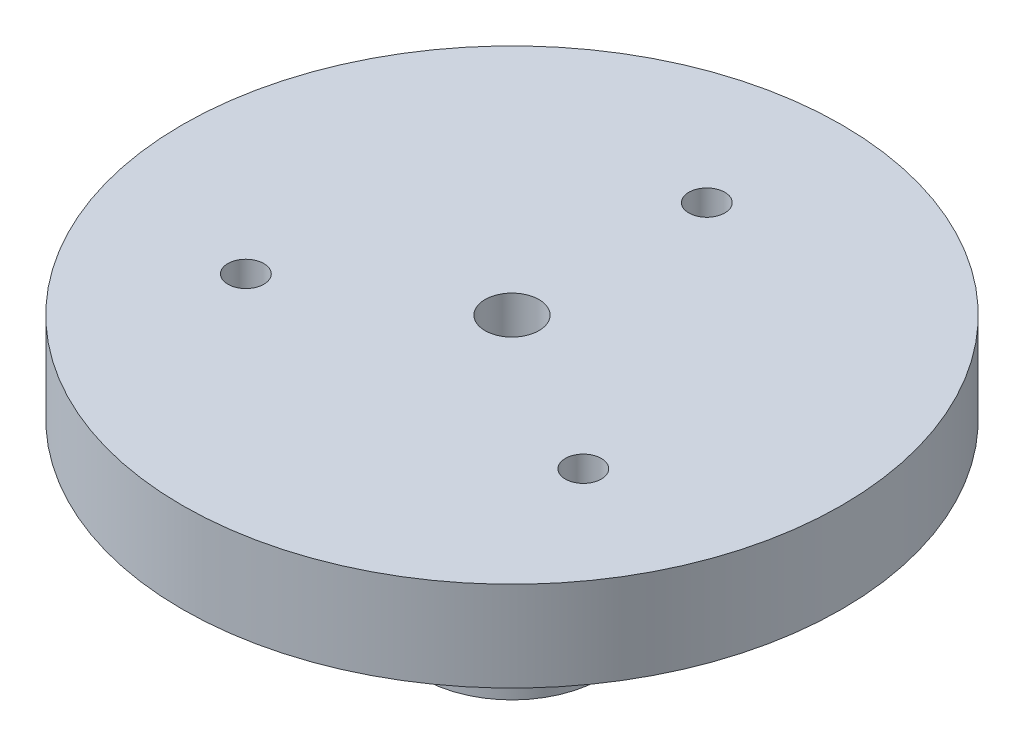
SolidWorks part; units mm, degrees
material "6061 Alloy"
ref_plane "Alzado" through (0, 0, 0) normal (0, 0, 1) x (1, 0, 0)
ref_plane "Planta" through (0, 0, 0) normal (0, 1, 0) x (1, 0, 0)
ref_plane "Vista lateral" through (0, 0, 0) normal (1, 0, 0) x (0, 0, -1)
ref_plane "Plane2" through (0, -164, 0) normal (0, 1, 0) x (1, 0, 0)
sketch "Sketch1" plane through (0, -164, 0) normal (0, 1, 0) x (1, 0, 0)
  circle A0 centre (0, 0) radius 11.0007
  circle A1 centre (0, 0) radius 0.9
  circle A2 centre (0, 6.5) radius 0.6
  circle A3 centre (-5.63, -3.25) radius 0.6
  circle A4 centre (5.63, -3.25) radius 0.6
extrude "Disco_aponeurosis" add sketch "Sketch1" along normal blind 3
sketch "Sketch2" plane through (0, 0, 0) normal (0, 0, 1) x (1, 0, 0)
  line L0 (0, -164) -> (3, -164)
  line L1 (3, -164) -> (3, -170)
  line L2 (3, -170) -> (1.2, -170)
  line L3 (1.2, -170) -> (0, -170)
  line L4 (0, -170) -> (0, -164)
  line L5 (0, -174) -> (0, -160) construction
revolve "Boca_tendon" add sketch "Sketch2" angle 360 about L5
